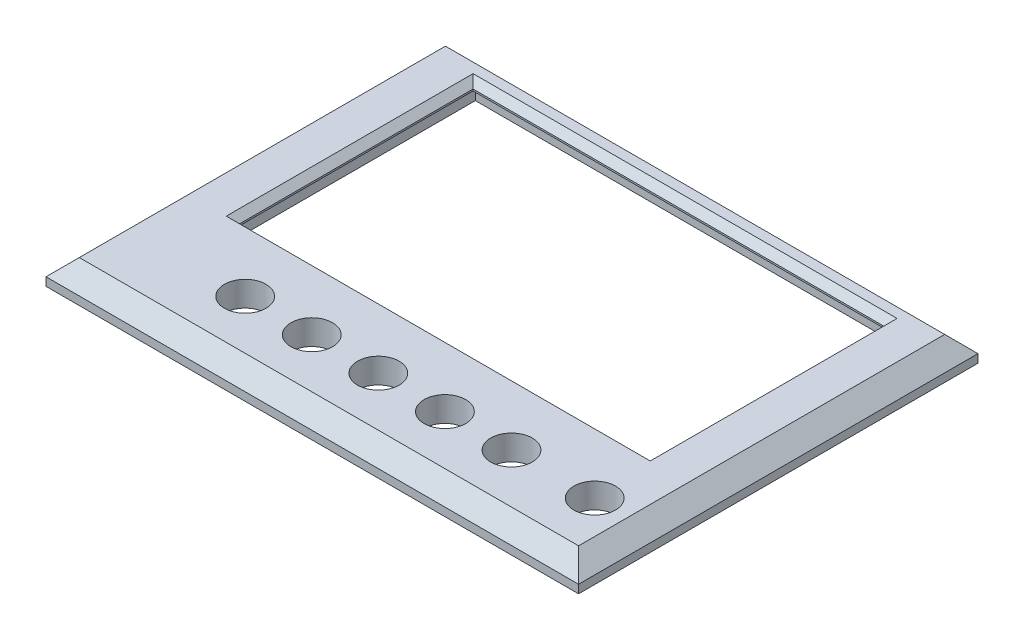
SolidWorks part; units mm, degrees
material "Mahogany"
ref_plane "Front Plane" through (0, 0, 0) normal (0, 0, 1) x (1, 0, 0)
ref_plane "Top Plane" through (0, 0, 0) normal (0, 1, 0) x (1, 0, 0)
ref_plane "Right Plane" through (0, 0, 0) normal (1, 0, 0) x (0, 0, -1)
sketch "Sketch1" plane through (0, 0, 0) normal (0, 1, 0) x (1, 0, 0)
  line L1 (-101.6, 76.2) -> (101.6, 76.2)
  line L2 (-101.6, 76.2) -> (-101.6, -76.2)
  line L3 (-101.6, -76.2) -> (101.6, -76.2)
  line L4 (101.6, 76.2) -> (101.6, -76.2)
  line L5 (-101.6, 76.2) -> (101.6, -76.2) construction
  line L6 (-101.6, -76.2) -> (101.6, 76.2) construction
  point P0 (0, 0)
  dimension "D1" = 203.2
  dimension "D2" = 152.4
extrude "Boss-Extrude1" add sketch "Sketch1" along normal blind 9.525
sketch "Sketch2" plane through (0, 9.525, 0) normal (0, 1, 0) x (1, 0, 0)
  line L0 (101.6, 76.2) -> (-101.6, 76.2) construction
  line L1 (-78.35, 63.5) -> (78.35, 63.5)
  line L2 (-78.35, 63.5) -> (-78.35, -25.6)
  line L3 (-78.35, -25.6) -> (78.35, -25.6)
  line L4 (78.35, 63.5) -> (78.35, -25.6)
  line L5 (-78.35, 63.5) -> (78.35, -25.6) construction
  line L6 (-78.35, -25.6) -> (78.35, 63.5) construction
  point P0 (0, 18.95)
  dimension "D1" = 156.7
  dimension "D2" = 89.1
  dimension "D3" = 12.7
extrude "Cut-Extrude1" cut sketch "Sketch2" against normal through all
chamfer "Chamfer1" distance 2.54 angle 45 4 edges at (78.35, 9.525, -18.95) (0, 9.525, 25.6) (-78.35, 9.525, -18.95) (0, 9.525, -63.5)
extrude "Cut-Extrude2" cut sketch "Sketch3" against normal blind 6.35
sketch "Sketch3" plane through (-44.7206, 0, -165.4534) normal (0, -1, 0) x (1, 0, 0)
  line L4 (-36.3394, 98.3834) -> (-36.3394, 198.3834)
  line L5 (128.5606, 98.3834) -> (-36.3394, 98.3834)
  line L6 (128.5606, 198.3834) -> (128.5606, 98.3834)
  line L7 (-36.3394, 198.3834) -> (128.5606, 198.3834)
sketch "Sketch4" plane through (0, 9.525, 0) normal (0, 1, 0) x (1, 0, 0)
  line L0 (-50.8, -51) -> (-25.4, -51) construction
  line L1 (-25.4, -51) -> (0, -51) construction
  line L2 (0, -51) -> (25.4, -51) construction
  line L3 (25.4, -51) -> (50.8, -51) construction
  line L4 (-78.35, -25.6) -> (78.35, -25.6) construction
  circle A0 centre (-50.8, -51) radius 7.9375
  circle A1 centre (-25.4, -51) radius 7.9375
  circle A2 centre (0, -51) radius 7.9375
  circle A3 centre (25.4, -51) radius 7.9375
  circle A4 centre (50.8, -51) radius 7.9375
  circle A5 centre (82.55, -51) radius 7.9375
  point P14 (0, 0)
  point P16 (82.9373, -51)
  point P17 (0, 0)
  point P18 (0, 0)
  dimension "D1" = 15.875
  dimension "D2" = 25.4
  dimension "D3" = 25.4
  dimension "D4" = 31.75
extrude "Cut-Extrude3" cut sketch "Sketch4" against normal through all
chamfer "Chamfer2" distance 6.35 angle 45 4 edges at (101.6, 9.525, 0) (0, 9.525, 76.2) (0, 9.525, -76.2) (-101.6, 9.525, 0)
